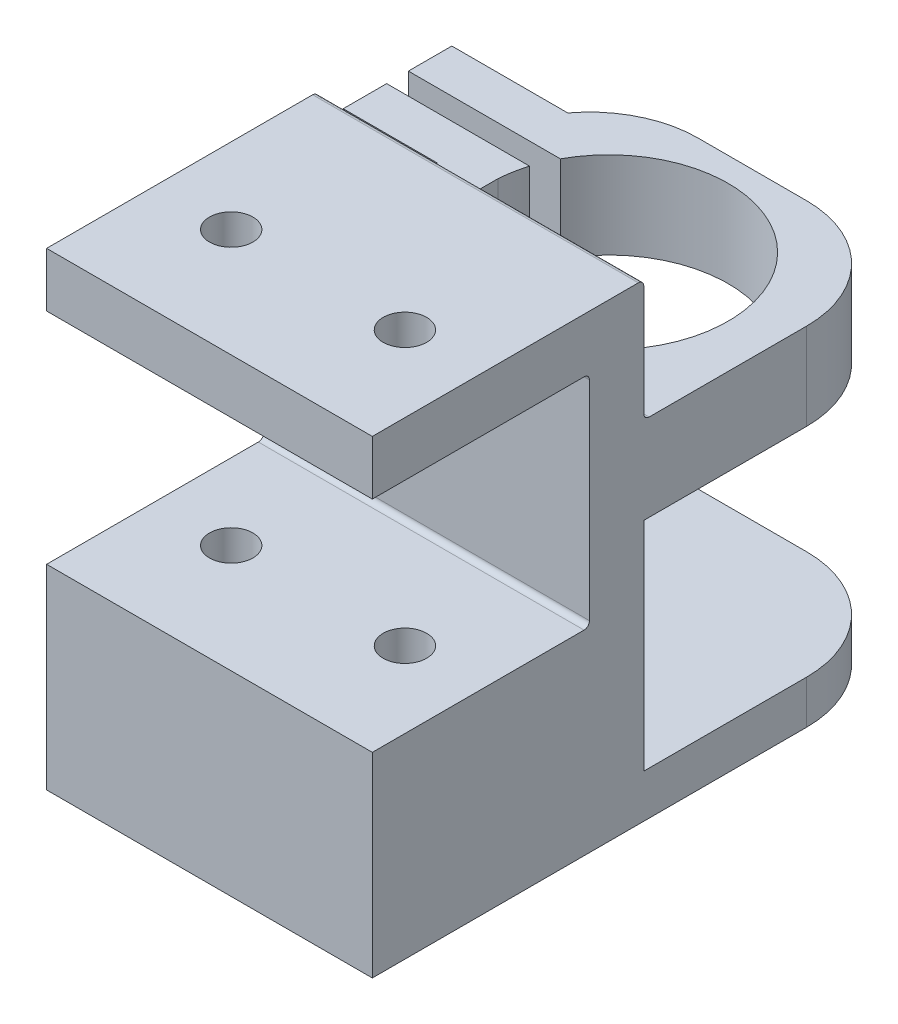
SolidWorks part; units mm, degrees
ref_plane "Front Plane" through (0, 0, 0) normal (0, 0, 1) x (1, 0, 0)
ref_plane "Top Plane" through (0, 0, 0) normal (0, 1, 0) x (1, 0, 0)
ref_plane "Right Plane" through (0, 0, 0) normal (1, 0, 0) x (0, 0, -1)
sketch "Sketch2" plane through (0, 0, 0) normal (1, 0, 0) x (0, 0, -1)
  line L1 (-10, -10.1) -> (10, -10.1) construction
  line L2 (-10, -10.1) -> (-10, 10.1) construction
  line L3 (-10, 10.1) -> (10, 10.1) construction
  line L4 (10, -10.1) -> (10, 10.1) construction
  line L5 (-10, -10.1) -> (10, 10.1) construction
  line L6 (-10, 10.1) -> (10, -10.1) construction
  line L7 (-10, 10.1) -> (10, 10.1)
  line L8 (-10, 10.1) -> (-10, 15.1)
  line L9 (-10, 15.1) -> (10, 15.1)
  line L10 (10, 10.1) -> (10, 15.1)
  line L11 (-10, -10.1) -> (10, -10.1)
  line L12 (-10, -10.1) -> (-10, -18.1)
  line L13 (-10, -18.1) -> (10, -18.1)
  line L14 (10, -10.1) -> (10, -18.1)
  line L15 (40, 3.9) -> (10, 3.9)
  line L16 (40, 3.9) -> (40, -4.1)
  line L17 (40, -4.1) -> (10, -4.1)
  line L18 (10, 3.9) -> (10, -4.1)
  line L19 (10, 15.1) -> (15, 15.1)
  line L20 (10, 15.1) -> (10, 3.9)
  line L21 (10, 3.9) -> (15, 3.9)
  line L22 (15, 15.1) -> (15, 3.9)
  line L23 (10, -18.1) -> (15, -18.1)
  line L24 (10, -18.1) -> (10, -4.1)
  line L25 (10, -4.1) -> (15, -4.1)
  line L26 (15, -18.1) -> (15, -4.1)
  point P0 (0, 0)
  dimension "D1" = 20
  dimension "D2" = 20.2
  dimension "D3" = 5
  dimension "D4" = 8
  dimension "D5" = 30
  dimension "D6" = 8
  dimension "D7" = 6
extrude "Boss-Extrude1" add sketch "Sketch2" along normal blind 30 contours L15 L18 L17 L16 | L22 L19 L10 L20 L15 | L7 L10 L9 L8 | L14 L11 L12 L13 | L23 L26 L17 L24 L14
sketch "Sketch3" plane through (0, 3.9, 0) normal (0, 1, 0) x (1, 0, 0)
  line L0 (30, 10) -> (0, 10) construction
  line L1 (30, 40) -> (15, 26.775) construction
  line L2 (15, 26.775) -> (0, 40) construction
  circle A0 centre (15, 26.775) radius 11
  dimension "D1" = 22
  dimension "D2" = 16.775
extrude "Cut-Extrude1" cut sketch "Sketch3" against normal through all
fillet "Fillet1" radius 10 2 edges at (0, -0.1, -40) (30, -0.1, -40)
fillet "Fillet2" radius 0.5 4 edges at (15, 15.1, -15) (15, -10.1, -10) (15, 10.1, -10) (15, 3.9, -15)
sketch "Sketch4" plane through (0, 15.1, 0) normal (0, 1, 0) x (1, 0, 0)
  line L0 (0, 10) -> (30, 10) construction
  line L1 (0, -10) -> (0, 14.5) construction
  line L2 (30, -10) -> (30, 14.5) construction
  line L3 (30, -10) -> (0, -10) construction
  line L4 (0, -10) -> (7, 0) construction
  line L5 (7, 0) -> (23, 0) construction
  line L6 (23, 0) -> (30, -10) construction
  circle A0 centre (7, 0) radius 2
  circle A1 centre (23, 0) radius 2
  dimension "D2" = 4
  dimension "D3" = 7
  dimension "D1" = 20
extrude "Cut-Extrude2" cut sketch "Sketch4" against normal through all
sketch "Sketch5" plane through (0, 3.9, 0) normal (0, 1, 0) x (1, 0, 0)
  line L1 (0, 30) -> (6, 30)
  line L2 (0, 30) -> (0, 32)
  line L3 (0, 32) -> (6, 32)
  line L4 (6, 30) -> (6, 32)
  arc A0 (10, 40) -> (0, 30) centre (10, 30) ccw construction
  dimension "D1" = 2
  dimension "D2" = 6
extrude "Cut-Extrude3" cut sketch "Sketch5" against normal through all
sketch "Sketch6" plane through (0, 3.9, 0) normal (0, 1, 0) x (1, 0, 0)
  line L0 (0, 30) -> (4.4834, 30) construction
  line L1 (5.3202, 32) -> (-8.6798, 32)
  line L2 (5.3202, 32) -> (5.3202, 36)
  line L3 (5.3202, 36) -> (-8.6798, 36)
  line L4 (-8.6798, 32) -> (-8.6798, 36)
  line L5 (4.0273, 26) -> (-8.6798, 26)
  line L6 (4.0273, 26) -> (4.0273, 30)
  line L7 (4.0273, 30) -> (-8.6798, 30)
  line L8 (-8.6798, 26) -> (-8.6798, 30)
  arc A0 (4.4834, 30) -> (5.3202, 32) centre (15, 26.775) ccw construction
  dimension "D1" = 4
  dimension "D2" = 4
  dimension "D3" = 14
extrude "Boss-Extrude2" add sketch "Sketch6" against normal up to surface (8 mm away) up to face at (13.433, -4.1, -28.8163)
sketch "Sketch7" plane through (0, 0, -36) normal (0, 0, -1) x (-1, 0, 0)
  line L0 (8.6798, 3.9) -> (0.6798, -4.1) construction
  line L1 (-2, -4.1) -> (8.6798, -4.1) construction
  line L2 (0.6798, -4.1) -> (0.6798, 3.9) construction
  line L3 (-2, 3.9) -> (8.6798, 3.9) construction
  line L4 (0.6798, 3.9) -> (8.6798, -4.1) construction
  line L5 (8.6798, -4.1) -> (8.6798, 3.9) construction
  circle A0 centre (4.6798, -0.1) radius 1.5
  dimension "D2" = 3
  dimension "D1" = 8
extrude "Cut-Extrude4" cut sketch "Sketch7" against normal through all both and the other way through all
sketch "Sketch8" plane through (0, -18.1, 0) normal (0, -1, 0) x (1, 0, 0)
  line L4 (0, 10) -> (0, -15)
  line L5 (0, -15) -> (30, -15)
  line L6 (30, -15) -> (30, 10)
  line L7 (30, 10) -> (0, 10)
  line L8 (0, 10) -> (0, -15)
  line L9 (0, -15) -> (30, -15)
  line L10 (30, -15) -> (30, 10)
  line L11 (30, 10) -> (0, 10)
  circle A0 centre (7, 0) radius 2 construction
  circle A1 centre (23, 0) radius 2 construction
  circle A2 centre (7, 0) radius 2
  circle A3 centre (23, 0) radius 2
  dimension "D1" = 0
extrude "Boss-Extrude3" add sketch "Sketch8" along normal blind 6
sketch "Sketch9" plane through (0, -24.1, 0) normal (0, -1, 0) x (1, 0, 0)
  line L0 (15, -15) -> (15, -40) construction
  line L1 (0, -15) -> (30, -15) construction
  line L2 (0, -30) -> (0, -15)
  line L4 (30, 10) -> (0, 10)
  line L5 (0, 10) -> (0, -15)
  line L6 (0, -15) -> (30, -15)
  line L7 (30, -15) -> (30, 10)
  line L8 (30, 10) -> (0, 10)
  line L9 (0, 10) -> (0, -15)
  line L11 (30, -15) -> (30, 10)
  line L19 (4.0273, -27.55) -> (4.0273, -26)
  line L20 (5.3202, -32) -> (-8.6798, -32)
  line L21 (-8.6798, -32) -> (-8.6798, -36)
  line L22 (-8.6798, -36) -> (2, -36)
  line L23 (10, -40) -> (20, -40)
  line L24 (30, -30) -> (30, -15)
  line L25 (30, -15) -> (0, -15)
  line L26 (0, -15) -> (0, -26)
  line L27 (0, -26) -> (-8.6798, -26)
  line L28 (-8.6798, -26) -> (-8.6798, -30)
  line L29 (-8.6798, -30) -> (4.4834, -30)
  line L34 (10, -40) -> (20, -40)
  line L35 (30, -30) -> (30, -15)
  arc A0 (10, -40) -> (0, -30) centre (10, -30) cw
  circle A1 centre (7, 0) radius 2
  circle A2 centre (7, 0) radius 2
  circle A3 centre (23, 0) radius 2
  circle A4 centre (23, 0) radius 2
  arc A8 (4.0273, -27.55) -> (4.4834, -30) centre (15, -26.775) ccw
  arc A9 (5.3202, -32) -> (4.0273, -26) centre (15, -26.775) ccw
  arc A10 (2, -36) -> (10, -40) centre (10, -30) ccw
  arc A11 (20, -40) -> (30, -30) centre (20, -30) ccw
  arc A15 (20, -40) -> (30, -30) centre (20, -30) ccw
  dimension "D1" = 0
  dimension "D2" = 0
  dimension "D3" = 0
  dimension "D4" = 0
extrude "Boss-Extrude4" add sketch "Sketch9" along normal blind 4
